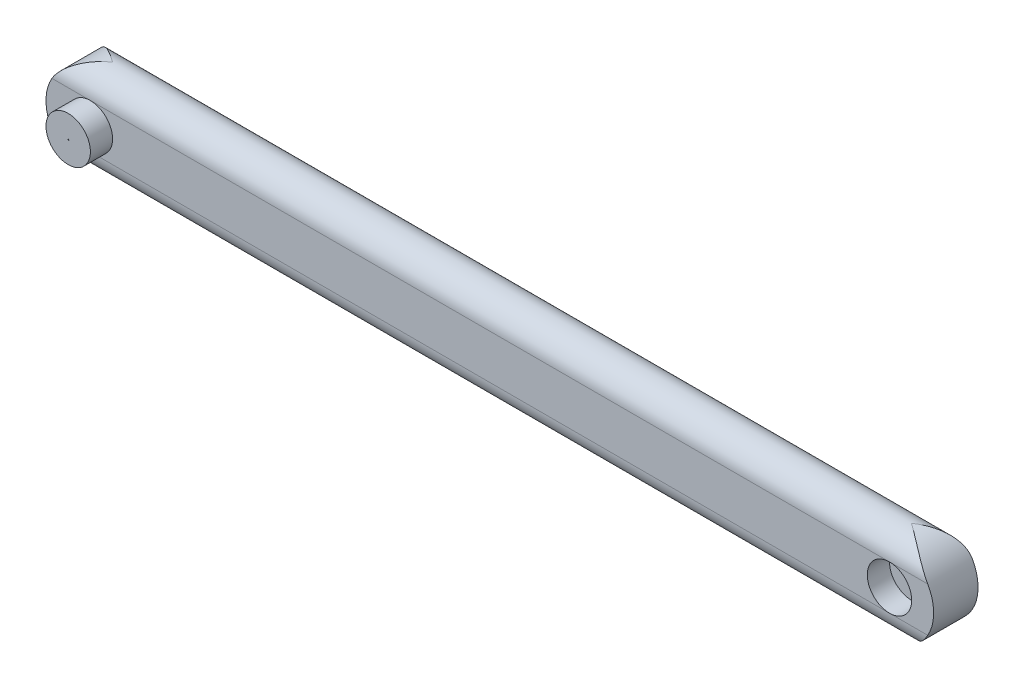
SolidWorks part; units mm, degrees
ref_plane "Front Plane" through (0, 0, 0) normal (0, 0, 1) x (1, 0, 0)
ref_plane "Top Plane" through (0, 0, 0) normal (0, 1, 0) x (1, 0, 0)
ref_plane "Right Plane" through (0, 0, 0) normal (1, 0, 0) x (0, 0, -1)
other "Center of Mass"
sketch "Sketch1" plane through (0, 0, 0) normal (1, 0, 0) x (0, 0, -1)
  line L2 (-50, 50) -> (-50, -50)
  line L4 (50, 50) -> (50, -50)
  arc A0 (50, 50) -> (-50, 50) centre (0, 50) ccw
  arc A1 (-50, -50) -> (50, -50) centre (0, -50) ccw
  point P0 (0, 0)
  dimension "D3" = 100
  dimension "D1" = 100
  dimension "D2" = 100
extrude "Boss-Extrude1" add sketch "Sketch1" against normal blind 2000
sketch "Sketch2" plane through (0, 0, 50) normal (0, 0, 1) x (1, 0, 0)
  line L0 (-2000, 50) -> (-2000, -50) construction
  line L1 (-1899.5, 100) -> (-2000, 100)
  line L2 (-2000, 100) -> (-2000, -100)
  line L3 (-2000, -100) -> (-1899.5, -100)
  line L4 (-100.5, 100) -> (0, 100)
  line L5 (0, 100) -> (0, -100)
  line L6 (0, -100) -> (-100.5, -100)
  arc A1 (-100.5, -100) -> (-100.5, 100) centre (-100.5, 0) ccw
  arc A2 (-1899.5, 100) -> (-1899.5, -100) centre (-1899.5, 0) ccw
  dimension "D1" = 100.5
  dimension "D2" = 100.5
extrude "Cut-Extrude1" cut sketch "Sketch2" against normal blind 100
sketch "Sketch3" plane through (0, 0, 50) normal (0, 0, 1) x (1, 0, 0)
  circle A0 centre (-100, 0) radius 50
  dimension "D1" = 100
  dimension "D2" = 100
extrude "Cut-Extrude2" cut sketch "Sketch3" against normal blind 50
sketch "Sketch4" plane through (0, 0, 50) normal (0, 0, 1) x (1, 0, 0)
  circle A0 centre (-1899.5, 0) radius 50
  arc A1 (-1986.1025, 50) -> (-1986.1025, -50) centre (-1899.5, 0) ccw construction
  point P5 (-1999.5, 0)
  dimension "D1" = 100
  dimension "D2" = 100
extrude "Boss-Extrude2" add sketch "Sketch4" along normal blind 50
sketch "Sketch5" plane through (0, 0, 100) normal (0, 0, 1) x (1, 0, 0)
  line L1 (-1899.5, 0) -> (-1897.6396, 0)
  line L2 (-1899.5, 0) -> (-1899.5, -2.1974)
  line L3 (-1899.5, -2.1974) -> (-1897.6396, -2.1974)
  line L4 (-1897.6396, 0) -> (-1897.6396, -2.1974)
extrude "Cut-Extrude3" cut sketch "Sketch5" against normal blind 1
